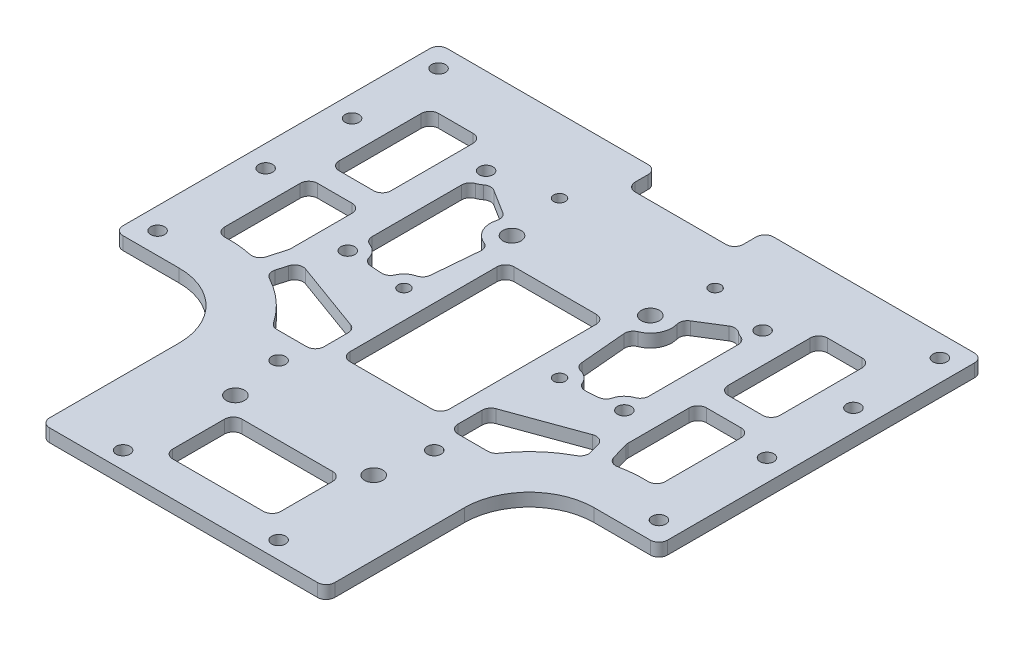
SolidWorks part; units mm, degrees
material "环氧树脂FR-4"
ref_plane "前视基准面" through (0, 0, 0) normal (0, 0, 1) x (1, 0, 0)
ref_plane "上视基准面" through (0, 0, 0) normal (0, 1, 0) x (1, 0, 0)
ref_plane "右视基准面" through (0, 0, 0) normal (1, 0, 0) x (0, 0, -1)
sketch "草图1" plane through (0, 0, 0) normal (0, 1, 0) x (1, 0, 0)
  line L1 (63, -55) -> (-63, -55)
  line L2 (63, -55) -> (63, 55)
  line L3 (63, 55) -> (-63, 55)
  line L4 (-63, -55) -> (-63, 55)
  line L5 (63, -55) -> (-63, 55) construction
  line L6 (63, 55) -> (-63, -55) construction
  point P0 (0, 0)
  dimension "D1" = 126
  dimension "D2" = 110
extrude "凸台-拉伸1" add sketch "草图1" along normal blind 3
sketch "草图2" plane through (0, 3, 0) normal (0, 1, 0) x (1, 0, 0)
  line L7 (63, 55) -> (-63, 55) construction
  line L8 (12.5, 48) -> (-12.5, 48)
  line L9 (12.5, 48) -> (12.5, 62)
  line L10 (12.5, 62) -> (-12.5, 62)
  line L11 (-12.5, 48) -> (-12.5, 62)
  line L12 (12.5, 48) -> (-12.5, 62) construction
  line L13 (12.5, 62) -> (-12.5, 48) construction
  point P7 (0, 55)
  dimension "D3" = 25
  dimension "D4" = 14
extrude "切除-拉伸1" cut sketch "草图2" against normal blind 10
sketch "草图3" plane through (0, 3, 0) normal (0, 1, 0) x (1, 0, 0)
  line L0 (0, 48) -> (0, 0) construction
  line L1 (-12.5, 48) -> (12.5, 48) construction
  line L2 (-16, -39) -> (-16, 25) construction
  circle A0 centre (-16, 25) radius 2.1
  circle A1 centre (-16, -39) radius 2.1
  circle A2 centre (16, -39) radius 2.1
  circle A3 centre (16, 25) radius 2.1
  dimension "D3" = 4.2
  dimension "D1" = 64
  dimension "D2" = 32
  dimension "D4" = 25
extrude "切除-拉伸2" cut sketch "草图3" against normal through all
sketch "草图4" plane through (0, 3, 0) normal (0, 1, 0) x (1, 0, 0)
  line L0 (0, 48) -> (0, -55) construction
  line L1 (-93, -90) -> (-33, -90)
  line L2 (-93, -90) -> (-93, -20)
  line L3 (-93, -20) -> (-33, -20)
  line L4 (-33, -90) -> (-33, -20)
  line L5 (-93, -90) -> (-33, -20) construction
  line L6 (-93, -20) -> (-33, -90) construction
  line L7 (-12.5, 48) -> (12.5, 48) construction
  line L8 (-63, -55) -> (63, -55) construction
  line L9 (93, -20) -> (33, -20)
  line L10 (33, -90) -> (33, -20)
  line L11 (93, -90) -> (33, -90)
  line L12 (93, -90) -> (93, -20)
  point P0 (-63, -55)
  dimension "D1" = 60
  dimension "D2" = 70
extrude "切除-拉伸3" cut sketch "草图4" against normal through all
sketch "草图5" plane through (0, 3, 0) normal (0, 1, 0) x (1, 0, 0)
  line L0 (-12.5, 55) -> (-63, 55) construction
  line L1 (11.5, -19) -> (-11.5, -19)
  line L2 (11.5, -19) -> (11.5, 19)
  line L3 (11.5, 19) -> (-11.5, 19)
  line L4 (-11.5, -19) -> (-11.5, 19)
  line L5 (11.5, -19) -> (-11.5, 19) construction
  line L6 (11.5, 19) -> (-11.5, -19) construction
  point P0 (0, 0)
  dimension "D1" = 36
  dimension "D2" = 23
  dimension "D3" = 38
extrude "切除-拉伸4" cut sketch "草图5" against normal through all
fillet "圆角1" radius 2 4 edges at (-11.5, 1.5, 19) (11.5, 1.5, 19) (11.5, 1.5, -19) (-11.5, 1.5, -19)
sketch "草图6" plane through (0, 3, 0) normal (0, 1, 0) x (1, 0, 0)
  line L0 (0, 48) -> (0, -55) construction
  line L1 (-12.5, 48) -> (12.5, 48) construction
  line L2 (-33, -55) -> (33, -55) construction
  line L3 (-58, 50) -> (-58, 10) construction
  line L4 (-12.5, 55) -> (-63, 55) construction
  line L5 (-63, 55) -> (-63, -20) construction
  circle A0 centre (-58, 50) radius 1.6
  circle A1 centre (-58, 10) radius 1.6
  circle A2 centre (-58, 30) radius 1.6
  circle A3 centre (58, 30) radius 1.6
  circle A4 centre (58, 10) radius 1.6
  circle A5 centre (58, 50) radius 1.6
  circle A6 centre (-58, -15) radius 1.6
  circle A7 centre (58, -15) radius 1.6
  dimension "D3" = 3.2
  dimension "D5" = 25
  dimension "D1" = 5
  dimension "D2" = 40
  dimension "D4" = 5
extrude "切除-拉伸5" cut sketch "草图6" against normal through all
fillet "圆角2" radius 15 2 edges at (33, 1.5, 20) (-33, 1.5, 20)
sketch "草图7" plane through (0, 3, 0) normal (0, 1, 0) x (1, 0, 0)
  line L0 (0, 48) -> (0, -55) construction
  line L1 (-12.5, 48) -> (12.5, 48) construction
  line L2 (-33, -55) -> (33, -55) construction
  line L3 (32, 35) -> (32, 3) construction
  line L4 (63, 55) -> (12.5, 55) construction
  circle A0 centre (32, 35) radius 1.6
  circle A1 centre (32, 3) radius 1.6
  circle A2 centre (-32, 3) radius 1.6
  circle A3 centre (-32, 35) radius 1.6
  dimension "D3" = 3.2
  dimension "D1" = 32
  dimension "D2" = 64
  dimension "D4" = 20
extrude "A板安装孔" cut sketch "草图7" against normal through all
sketch "草图8" plane through (0, 3, 0) normal (0, 1, 0) x (1, 0, 0)
  line L0 (0, 0) -> (0, -83.1609) construction
  line L3 (-18, 2) -> (18, 2) construction
  line L4 (-18, 2) -> (-18, 38) construction
  line L5 (-18, 38) -> (18, 38) construction
  line L6 (18, 2) -> (18, 38) construction
  line L7 (-18, 2) -> (18, 38) construction
  line L8 (-18, 38) -> (18, 2) construction
  circle A0 centre (18, 38) radius 1.35
  circle A1 centre (18, 2) radius 1.35
  circle A2 centre (-18, 2) radius 1.35
  circle A3 centre (-18, 38) radius 1.35
  point P4 (0, 20)
  dimension "D4" = 2.7
  dimension "D1" = 36
  dimension "D2" = 36
  dimension "D3" = 20
extrude "C板安装孔" cut sketch "草图8" against normal through all
sketch "草图9" plane through (0, 3, 0) normal (0, 1, 0) x (1, 0, 0)
  line L0 (0, 0) -> (0, 48) construction
  line L1 (-12.5, 48) -> (12.5, 48) construction
sketch "草图10" plane through (0, 0, 0) normal (0, 1, 0) x (1, 0, 0)
  line L0 (0, 0) -> (0, -55) construction
  line L1 (-33, -55) -> (33, -55) construction
  line L2 (63, 55) -> (37.75, 103.7139)
  line L3 (63, 55) -> (12.5, 55) construction
  line L4 (22, 103.7139) -> (22, 55)
  line L5 (37.75, 103.7139) -> (22, 103.7139)
  line L6 (-37.75, 103.7139) -> (-22, 103.7139)
  line L7 (-22, 103.7139) -> (-22, 55)
  line L8 (-63, 55) -> (-37.75, 103.7139)
  line L9 (-63, 55) -> (-22, 55)
  line L10 (22, 55) -> (63, 55)
  dimension "D1" = 44
extrude "凸台-拉伸2" [suppressed] add sketch "草图10" along normal up to surface (3 mm away)
sketch "草图11" plane through (0, 0, 0) normal (0, 1, 0) x (1, 0, 0)
  line L0 (-33, -55) -> (-33, -67)
  line L1 (-33, -67) -> (33, -67)
  line L2 (33, -67) -> (33, -55)
  line L3 (33, -55) -> (-33, -55)
  dimension "D1" = 12
extrude "凸台-拉伸3" add sketch "草图11" along normal up to surface (3 mm away) up to face at (-18, 3, -0.65)
sketch "草图12" plane through (0, 3, 0) normal (0, 1, 0) x (1, 0, 0)
  line L0 (0, 0) -> (0, -45) construction
  line L1 (18, -63) -> (-18, -63) construction
  line L2 (18, -63) -> (18, -27) construction
  line L3 (18, -27) -> (-18, -27) construction
  line L4 (-18, -63) -> (-18, -27) construction
  line L5 (18, -63) -> (-18, -27) construction
  line L6 (18, -27) -> (-18, -63) construction
  line L7 (-33, -67) -> (33, -67) construction
  circle A0 centre (-18, -27) radius 1.6
  circle A1 centre (18, -27) radius 1.6
  circle A2 centre (-18, -63) radius 1.6
  circle A3 centre (18, -63) radius 1.6
  point P0 (0, -45)
  dimension "D3" = 3.2
  dimension "D1" = 36
  dimension "D2" = 4
extrude "切除-拉伸6" cut sketch "草图12" against normal through all
sketch "草图14" plane through (0, 3, 0) normal (0, 1, 0) x (1, 0, 0)
  line L0 (0, 0) -> (0, -51) construction
  line L1 (12.5, -59) -> (-12.5, -59)
  line L2 (12.5, -59) -> (12.5, -43)
  line L3 (12.5, -43) -> (-12.5, -43)
  line L4 (-12.5, -59) -> (-12.5, -43)
  line L5 (12.5, -59) -> (-12.5, -43) construction
  line L6 (12.5, -43) -> (-12.5, -59) construction
  line L7 (-33, -67) -> (33, -67) construction
  circle A0 centre (-16, -39) radius 2.1 construction
  point P0 (0, -51)
  dimension "D1" = 8
  dimension "D2" = 4
  dimension "D3" = 25
extrude "切除-拉伸8" cut sketch "草图14" against normal through all
fillet "圆角3" radius 2 14 edges at (63, 1.5, 20) (63, 1.5, -55) (12.5, 1.5, -55) (12.5, 1.5, -48) (-12.5, 1.5, -48) (-12.5, 1.5, -55) (-63, 1.5, -55) (-63, 1.5, 20) (-33, 1.5, 67) (33, 1.5, 67) (12.5, 1.5, 43) (12.5, 1.5, 59) (-12.5, 1.5, 59) (-12.5, 1.5, 43)
sketch "草图13" plane through (0, 3, 0) normal (0, 1, 0) x (1, 0, 0)
  line L0 (-32, 35) -> (-16, 25)
  line L1 (-16, 25) -> (-18, 2)
  line L2 (-18, 2) -> (-32, 3)
  line L3 (-32, 35) -> (-32, 3)
  line L4 (-39, 41) -> (-39, 18)
  line L5 (-39, 18) -> (-51, 18)
  line L6 (-51, 18) -> (-51, 41)
  line L7 (-51, 41) -> (-39, 41)
  line L8 (-39, 13) -> (-39, -3.4467)
  line L9 (-25.5, -21) -> (-51, -21)
  line L10 (-51, -21) -> (-51, 13)
  line L11 (-51, 13) -> (-39, 13)
  line L12 (-25.5, -21) -> (-15.5, -21)
  line L13 (-15.5, -21) -> (-15.5, -12)
  line L14 (-15.5, -12) -> (-39, -3.4467)
  line L15 (-11.5, 17) -> (-11.5, -17) construction
  line L16 (-63, 53) -> (-63, -18) construction
  line L18 (-12.5, 55) -> (-63, 55) construction
  line L19 (-39, -3.4467) -> (-40.7313, -9.5164)
  line L20 (-36.968, -10.9055) -> (-35.2317, -4.8183)
  circle A0 centre (-32, 35) radius 4
  circle A1 centre (-32, 3) radius 4
  circle A2 centre (-18, 2) radius 4
  circle A3 centre (-16, 25) radius 5
  circle A4 centre (-48, -35) radius 26.5
  circle A5 centre (-18, -27) radius 1.6 construction
  dimension "D1" = 8
  dimension "D2" = 10
  dimension "D3" = 6
  dimension "D4" = 53
  dimension "D5" = 4
  dimension "D6" = 9
  dimension "D7" = 110
  dimension "D8" = 7
  dimension "D9" = 12
  dimension "D10" = 5
  dimension "D11" = 14
  dimension "D12" = 23
  dimension "D13" = 4
extrude "切除-拉伸7" cut sketch "草图13" against normal blind 10 contours L7 L6 L5 L4 | A3 L0 A0 L3 A1 L2 A2 L1 | A4 L19 L8 L11 L10 | A4 L12 L13 L14 L20
fillet "圆角4" radius 2 22 edges at (-16.4331, 1.5, -20.0188) (-17.6535, 1.5, -5.985) (-21.9898, 1.5, -2.285) (-28.0102, 1.5, -2.715) (-32, 1.5, -7) (-32, 1.5, -31) (-20.24, 1.5, -27.65) (-36.968, 1.5, 10.9055) (-35.2317, 1.5, 4.8183) (-15.5, 1.5, 12) (-15.5, 1.5, 21) (-25.5, 1.5, 21) (-39, 1.5, -41) (-39, 1.5, -18) (-51, 1.5, -18) (-51, 1.5, 8.6704) (-51, 1.5, -13) (-39, 1.5, -13) (-39, 1.5, 3.4467) (-40.7313, 1.5, 9.5164) (-51, 1.5, -41) (-28.608, 1.5, -32.88)
mirror "镜向1" about plane through (0, 0, 0) normal (1, 0, 0) of "圆角4", "切除-拉伸7"
